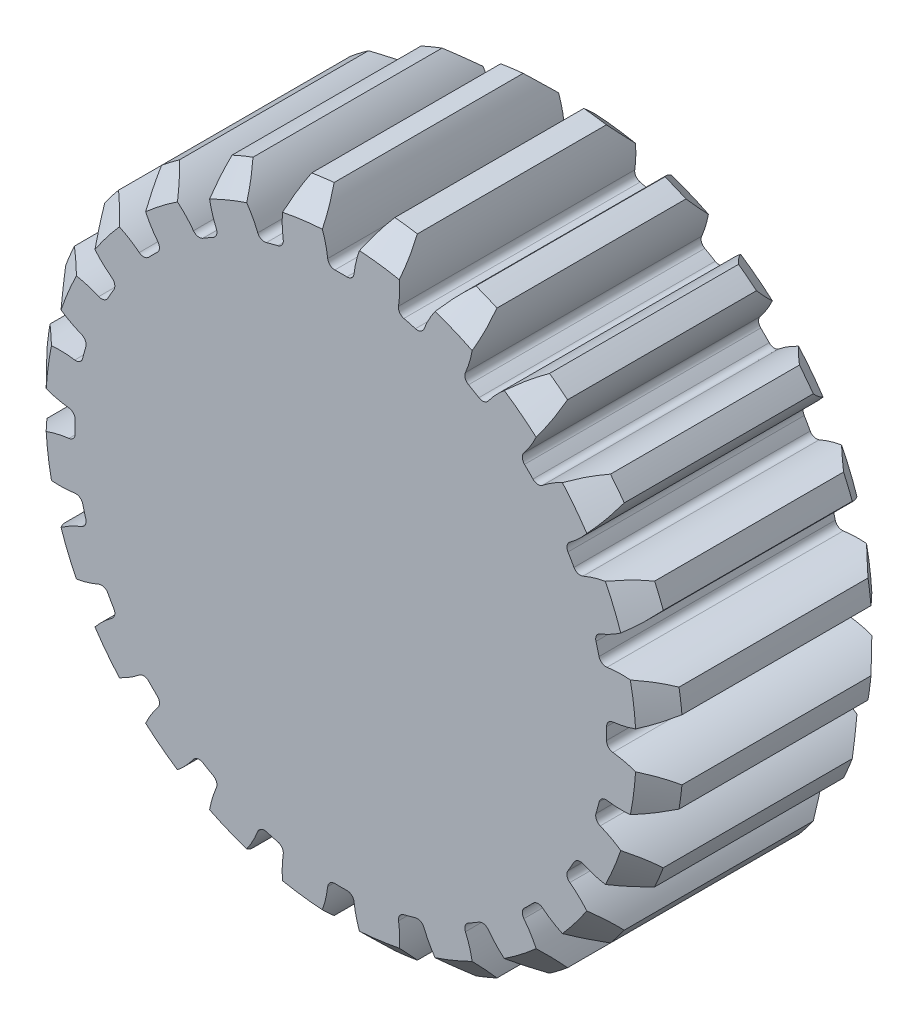
SolidWorks part; units mm, degrees
material "Plain Carbon Steel"
ref_plane "Front Plane" through (0, 0, 0) normal (0, 0, 1) x (1, 0, 0)
ref_plane "Top Plane" through (0, 0, 0) normal (0, 1, 0) x (1, 0, 0)
ref_plane "Right Plane" through (0, 0, 0) normal (1, 0, 0) x (0, 0, -1)
sketch "Sketch1" plane through (0, 0, 0) normal (0, 0, 1) x (1, 0, 0)
  circle A0 centre (0, 0) radius 25 construction
  circle A1 centre (0, 0) radius 27
  dimension "D1" = 50
  dimension "D2" = 54
extrude "Boss-Extrude1" add sketch "Sketch1" along normal mid plane 20
sketch "Sketch3" plane through (0, 0, 10) normal (0, 0, 1) x (1, 0, 0)
  line L0 (0, 0) -> (0, 27) construction
  line L1 (0, 0) -> (6.7146, 26.1517) construction
  line L2 (0, 0) -> (3.384, 26.7871) construction
  line L3 (-1.072, 22.4744) -> (0, 0) construction
  line L4 (-1.5698, 24.9507) -> (1.5698, 24.9507) construction
  line L5 (1.5698, 24.9507) -> (4.6845, 24.5572) construction
  line L6 (-2.2805, 26.9035) -> (0, 20.6378) construction
  circle A0 centre (0, 0) radius 23 construction
  arc A1 (1.072, 22.4744) -> (-1.072, 22.4744) centre (0, 0) ccw
  circle A2 centre (0, 0) radius 27 construction
  arc A3 (-2.5691, 26.8775) -> (-1.072, 22.4744) centre (-9.4743, 22.0737) cw
  arc A4 (2.5691, 26.8775) -> (1.072, 22.4744) centre (9.4743, 22.0737) ccw
  circle A5 centre (0, 0) radius 25 construction
  circle A6 centre (0, 0) radius 27 construction
  arc A7 (-2.5691, 26.8775) -> (2.5691, 26.8775) centre (0, 0) cw
  dimension "D1" = 14.4
  dimension "D2" = 7.2
  dimension "D3" = 4
  dimension "D4" = 4.5
  dimension "D5" = 20
extrude "Cut-Extrude1" cut sketch "Sketch3" against normal through all both and the other way through all
fillet "Fillet1" radius 0.6 2 edges at (-1.072, 22.4744, 0) (1.072, 22.4744, 0)
chamfer "Chamfer1" distance 2 2 edges at (0, -27, 10) (0, -27, -10)
pattern_circular "CirPattern1" count 25 every 15 about axis through (0, 0, 0) along (0, 0, 1) of "Fillet1", "Cut-Extrude1"
equation "\"Module\"= 2mm"
equation "\"Number of teeth\"= 25"
equation "\"Pressure Angle\"= 20"
equation "\"D1@Sketch1\"=\"Module\" * \"Number of teeth\""
equation "\"D2@Sketch1\"=(\"Number of teeth\" + 2 ) * \"Module\""
equation "\"D1@Sketch3\"=360 / \"Number of teeth\""
equation "\"D3@Sketch3\"=\"Module\"*2"
equation "\"D4@Sketch3\"=\"Module\" * if(\"Module\" => 1.25,2.25,2.4)"
equation "\"D5@Sketch3\"=\"Pressure Angle\""
equation "\"D1@Fillet1\"=0.3 * \"Module\""
equation "\"D1@CirPattern1\"=\"Number of teeth\""
equation "\"D1@Chamfer1\"=\"Module\""
